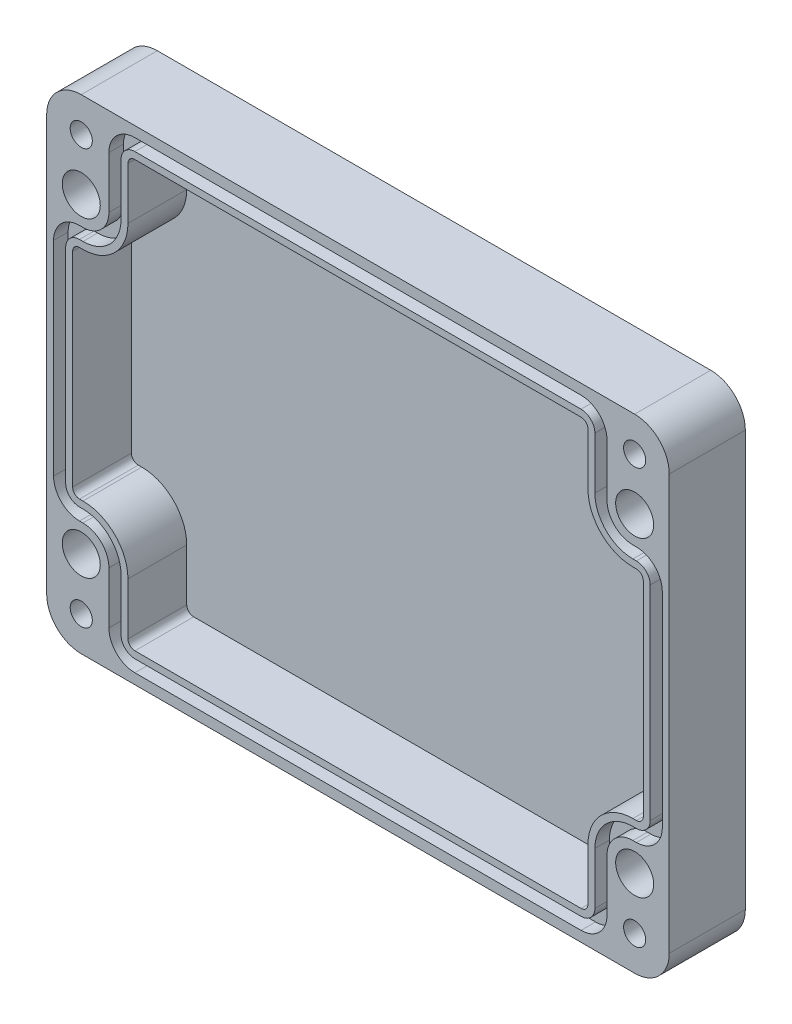
SolidWorks part; units mm, degrees
material "ألمنيوم خلائطي"
ref_plane "Front" through (0, 0, 0) normal (0, 0, 1) x (1, 0, 0)
ref_plane "Top" through (0, 0, 0) normal (0, 1, 0) x (1, 0, 0)
ref_plane "Right" through (0, 0, 0) normal (1, 0, 0) x (0, 0, -1)
sketch "Sketch1" plane through (0, 0, 0) normal (0, 0, 1) x (1, 0, 0)
  line L0 (90, 70) -> (-90, -70) construction
  line L1 (-90, 70) -> (90, 70)
  line L2 (-90, 70) -> (-90, -70)
  line L3 (-90, -70) -> (90, -70)
  line L4 (90, 70) -> (90, -70)
  dimension "D1" = 180
  dimension "D2" = 140
extrude "Boss-Extrude1" add sketch "Sketch1" along normal blind 22
sketch "Sketch2" plane through (0, 0, 22) normal (0, 0, 1) x (1, 0, 0)
  line L0 (-66.5, 61.5) -> (66.5, -61.5) construction
  line L1 (-66.5, 61.5) -> (66.5, 61.5)
  line L2 (-66.5, 61.5) -> (-66.5, 31.5)
  line L3 (-66.5, -61.5) -> (66.5, -61.5)
  line L4 (66.5, 61.5) -> (66.5, 31.5)
  line L5 (-82.5, 31.5) -> (-66.5, 31.5)
  line L6 (-82.5, 31.5) -> (-82.5, -31.5)
  line L7 (-82.5, -31.5) -> (-66.5, -31.5)
  line L8 (82.5, 31.5) -> (82.5, -31.5)
  line L9 (82.5, 31.5) -> (-82.5, -31.5) construction
  line L10 (66.5, 31.5) -> (82.5, 31.5)
  line L11 (66.5, -31.5) -> (82.5, -31.5)
  line L12 (66.5, -31.5) -> (66.5, -61.5)
  line L13 (-66.5, -31.5) -> (-66.5, -61.5)
  dimension "D1" = 123
  dimension "D2" = 133
  dimension "D3" = 165
  dimension "D4" = 63
extrude "Cut-Extrude1" cut sketch "Sketch2" against normal blind 17
fillet "Fillet1" radius 2 8 edges at (-66.5, -61.5, 13.5) (66.5, -61.5, 13.5) (66.5, 61.5, 13.5) (-66.5, 61.5, 13.5) (82.5, 31.5, 13.5) (82.5, -31.5, 13.5) (-82.5, -31.5, 13.5) (-82.5, 31.5, 13.5)
fillet "Fillet2" radius 13 4 edges at (66.5, 31.5, 13.5) (66.5, -31.5, 13.5) (-66.5, -31.5, 13.5) (-66.5, 31.5, 13.5)
sketch "Sketch3" plane through (0, 0, 22) normal (0, 0, 1) x (1, 0, 0)
  line L12 (-72, 59.5) -> (-72, 44.5)
  line L13 (64.5, 67) -> (-64.5, 67)
  line L14 (72, 44.5) -> (72, 59.5)
  line L15 (80.5, 37) -> (79.5, 37)
  line L16 (88, -29.5) -> (88, 29.5)
  line L17 (79.5, -37) -> (80.5, -37)
  line L18 (72, -59.5) -> (72, -44.5)
  line L19 (-64.5, -67) -> (64.5, -67)
  line L20 (-72, -44.5) -> (-72, -59.5)
  line L21 (-80.5, -37) -> (-79.5, -37)
  line L22 (-88, 29.5) -> (-88, -29.5)
  line L23 (-79.5, 37) -> (-80.5, 37)
  line L24 (-80.5, -33.5) -> (-79.5, -33.5)
  line L25 (-68.5, -44.5) -> (-68.5, -59.5)
  line L26 (-64.5, -63.5) -> (64.5, -63.5)
  line L27 (68.5, -59.5) -> (68.5, -44.5)
  line L28 (79.5, -33.5) -> (80.5, -33.5)
  line L29 (84.5, -29.5) -> (84.5, 29.5)
  line L30 (80.5, 33.5) -> (79.5, 33.5)
  line L31 (68.5, 44.5) -> (68.5, 59.5)
  line L32 (64.5, 63.5) -> (-64.5, 63.5)
  line L33 (-68.5, 59.5) -> (-68.5, 44.5)
  line L34 (-79.5, 33.5) -> (-80.5, 33.5)
  line L35 (-84.5, 29.5) -> (-84.5, -29.5)
  line L36 (-80.5, -33.5) -> (-79.5, -33.5)
  line L37 (-68.5, -44.5) -> (-68.5, -59.5)
  line L38 (-64.5, -63.5) -> (64.5, -63.5)
  line L39 (68.5, -59.5) -> (68.5, -44.5)
  line L40 (79.5, -33.5) -> (80.5, -33.5)
  line L41 (84.5, -29.5) -> (84.5, 29.5)
  line L42 (80.5, 33.5) -> (79.5, 33.5)
  line L43 (68.5, 44.5) -> (68.5, 59.5)
  line L44 (64.5, 63.5) -> (-64.5, 63.5)
  line L45 (-68.5, 59.5) -> (-68.5, 44.5)
  line L46 (-79.5, 33.5) -> (-80.5, 33.5)
  line L47 (-84.5, 29.5) -> (-84.5, -29.5)
  arc A12 (-79.5, 37) -> (-72, 44.5) centre (-79.5, 44.5) ccw
  arc A13 (-64.5, 67) -> (-72, 59.5) centre (-64.5, 59.5) ccw
  arc A14 (72, 59.5) -> (64.5, 67) centre (64.5, 59.5) ccw
  arc A15 (72, 44.5) -> (79.5, 37) centre (79.5, 44.5) ccw
  arc A16 (88, 29.5) -> (80.5, 37) centre (80.5, 29.5) ccw
  arc A17 (80.5, -37) -> (88, -29.5) centre (80.5, -29.5) ccw
  arc A18 (79.5, -37) -> (72, -44.5) centre (79.5, -44.5) ccw
  arc A19 (64.5, -67) -> (72, -59.5) centre (64.5, -59.5) ccw
  arc A20 (-72, -59.5) -> (-64.5, -67) centre (-64.5, -59.5) ccw
  arc A21 (-72, -44.5) -> (-79.5, -37) centre (-79.5, -44.5) ccw
  arc A22 (-88, -29.5) -> (-80.5, -37) centre (-80.5, -29.5) ccw
  arc A23 (-80.5, 37) -> (-88, 29.5) centre (-80.5, 29.5) ccw
  arc A24 (-68.5, -44.5) -> (-79.5, -33.5) centre (-79.5, -44.5) ccw
  arc A25 (-68.5, -59.5) -> (-64.5, -63.5) centre (-64.5, -59.5) ccw
  arc A26 (64.5, -63.5) -> (68.5, -59.5) centre (64.5, -59.5) ccw
  arc A27 (79.5, -33.5) -> (68.5, -44.5) centre (79.5, -44.5) ccw
  arc A28 (80.5, -33.5) -> (84.5, -29.5) centre (80.5, -29.5) ccw
  arc A29 (84.5, 29.5) -> (80.5, 33.5) centre (80.5, 29.5) ccw
  arc A30 (68.5, 44.5) -> (79.5, 33.5) centre (79.5, 44.5) ccw
  arc A31 (68.5, 59.5) -> (64.5, 63.5) centre (64.5, 59.5) ccw
  arc A32 (-64.5, 63.5) -> (-68.5, 59.5) centre (-64.5, 59.5) ccw
  arc A33 (-79.5, 33.5) -> (-68.5, 44.5) centre (-79.5, 44.5) ccw
  arc A34 (-80.5, 33.5) -> (-84.5, 29.5) centre (-80.5, 29.5) ccw
  arc A35 (-84.5, -29.5) -> (-80.5, -33.5) centre (-80.5, -29.5) ccw
  arc A36 (-68.5, -44.5) -> (-79.5, -33.5) centre (-79.5, -44.5) ccw
  arc A37 (-68.5, -59.5) -> (-64.5, -63.5) centre (-64.5, -59.5) ccw
  arc A38 (64.5, -63.5) -> (68.5, -59.5) centre (64.5, -59.5) ccw
  arc A39 (79.5, -33.5) -> (68.5, -44.5) centre (79.5, -44.5) ccw
  arc A40 (80.5, -33.5) -> (84.5, -29.5) centre (80.5, -29.5) ccw
  arc A41 (84.5, 29.5) -> (80.5, 33.5) centre (80.5, 29.5) ccw
  arc A42 (68.5, 44.5) -> (79.5, 33.5) centre (79.5, 44.5) ccw
  arc A43 (68.5, 59.5) -> (64.5, 63.5) centre (64.5, 59.5) ccw
  arc A44 (-64.5, 63.5) -> (-68.5, 59.5) centre (-64.5, 59.5) ccw
  arc A45 (-79.5, 33.5) -> (-68.5, 44.5) centre (-79.5, 44.5) ccw
  arc A46 (-80.5, 33.5) -> (-84.5, 29.5) centre (-80.5, 29.5) ccw
  arc A47 (-84.5, -29.5) -> (-80.5, -33.5) centre (-80.5, -29.5) ccw
  dimension "D1" = 2
  dimension "D2" = 3.5
extrude "Cut-Extrude2" cut sketch "Sketch3" against normal blind 4.2
fillet "Fillet3" radius 10 4 edges at (-90, -70, 11) (-90, 70, 11) (90, 70, 11) (90, -70, 11)
hole_wizard "Ø11.0 (11) Diameter Hole1" positions "Sketch5" profile "Sketch4" hole size "Ø11.0" standard "ISO" end condition up to next
sketch "Sketch5" plane through (0, 0, 22) normal (0, 0, 1) x (1, 0, 0)
  line L0 (-80, 45) -> (80, 45) construction
  line L1 (80, 45) -> (80, -45) construction
  line L2 (80, -45) -> (-80, -45) construction
  line L3 (-80, -45) -> (-80, 45) construction
  line L5 (-80, -45) -> (80, 45) construction
  point P0 (-80, 45)
  point P1 (-80, -45)
  point P3 (80, -45)
  point P5 (80, 45)
  dimension "D1" = 160
  dimension "D2" = 90
sketch "Sketch4" plane through (-80, 45, 22) normal (1, 0, 0) x (0, -1, 0)
  line L0 (0, 0) -> (0, 22)
  line L1 (0, 22) -> (5.5, 22)
  line L2 (5.5, 22) -> (5.5, 0)
  line L5 (5.5, 0) -> (0, 0)
  line L11 (0, -6.35) -> (0, 107.95) construction
  dimension "Thru Hole Dia." = 11
  dimension "Thru Hole Depth" = 22
hole_wizard "M6 Clearance Hole1" positions "Sketch7" profile "Sketch6" hole size "M6" standard "ISO" end condition up to next
sketch "Sketch7" plane through (0, 0, 22) normal (0, 0, 1) x (1, 0, 0)
  line L0 (-80, 60) -> (80, 60) construction
  line L1 (80, 60) -> (80, -60) construction
  line L2 (80, -60) -> (-80, -60) construction
  line L3 (-80, -60) -> (-80, 60) construction
  line L5 (-80, -60) -> (80, 60) construction
  line L7 (-80, 45) -> (-80, 60) construction
  point P0 (-80, 60)
  point P1 (-80, -60)
  point P3 (80, -60)
  point P5 (80, 60)
  dimension "D1" = 120
sketch "Sketch6" plane through (-80, 60, 22) normal (1, 0, 0) x (0, -1, 0)
  line L0 (0, 0) -> (0, 22)
  line L1 (0, 22) -> (3.2, 22)
  line L2 (3.2, 22) -> (3.2, 0)
  line L5 (3.2, 0) -> (0, 0)
  line L11 (0, -6.35) -> (0, 107.95) construction
  dimension "Thru Hole Dia." = 6.4
  dimension "Thru Hole Depth" = 22
sketch "Sketch11" plane through (0, 0, 0) normal (0, 0, -1) x (-1, 0, 0)
  circle A0 centre (-80, 60) radius 5.5
  circle A1 centre (-80, -60) radius 5.5
  circle A2 centre (80, -60) radius 5.5
  circle A3 centre (80, 60) radius 5.5
  dimension "D1" = 11
extrude "Cut-Extrude6" cut sketch "Sketch11" against normal blind 7
